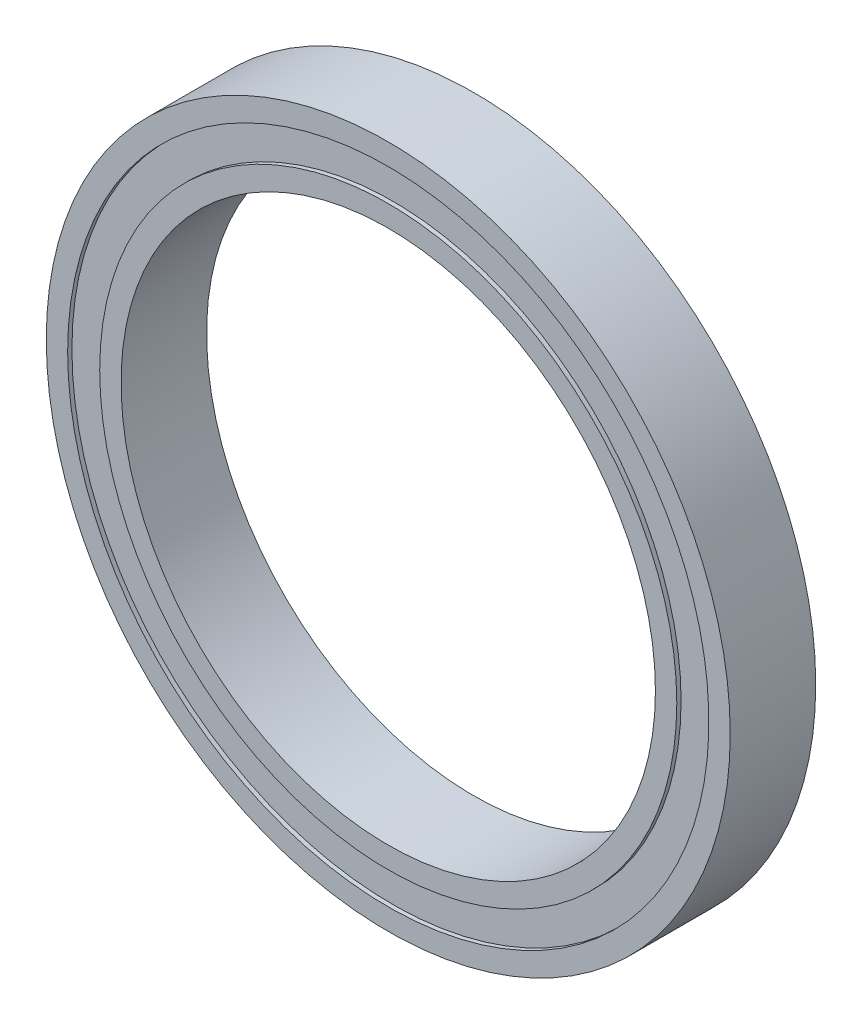
SolidWorks part; units mm, degrees
ref_plane "Plan de face" through (0, 0, 0) normal (0, 0, 1) x (1, 0, 0)
ref_plane "Plan de dessus" through (0, 0, 0) normal (0, 1, 0) x (1, 0, 0)
ref_plane "Plan de droite" through (0, 0, 0) normal (1, 0, 0) x (0, 0, -1)
sketch "Esquisse1" plane through (0, 0, 0) normal (0, 0, 1) x (1, 0, 0)
  circle A0 centre (0, 0) radius 16
  circle A1 centre (0, 0) radius 12.5
  dimension "D1" = 32
  dimension "D2" = 25
extrude "Boss.-Extru.1" add sketch "Esquisse1" along normal mid plane 4
sketch "Esquisse2" plane through (0, 0, 0) normal (1, 0, 0) x (0, 0, -1)
  line L0 (0, 0) -> (-3.9769, 0) construction
  line L1 (-2, 16) -> (-2, 12.5) construction
  line L2 (-2, 14.25) -> (-1.8, 14.25) construction
  line L3 (-1.8, 15) -> (-1.8, 13.5)
  line L4 (-1.8, 15) -> (-2, 15)
  line L5 (-2, 15) -> (-2, 13.5)
  line L6 (-2, 13.5) -> (-1.8, 13.5)
  line L7 (0, 0) -> (0, 3.3493) construction
  line L8 (2, 13.5) -> (1.8, 13.5)
  line L9 (1.8, 15) -> (1.8, 13.5)
  line L10 (1.8, 15) -> (2, 15)
  line L11 (2, 15) -> (2, 13.5)
  point P11 (-1.8, 14.25)
  dimension "D1" = 1
  dimension "D2" = 0.2
revolve "Enlèvement de matière-Révolution1" cut sketch "Esquisse2" angle 360 about L0
